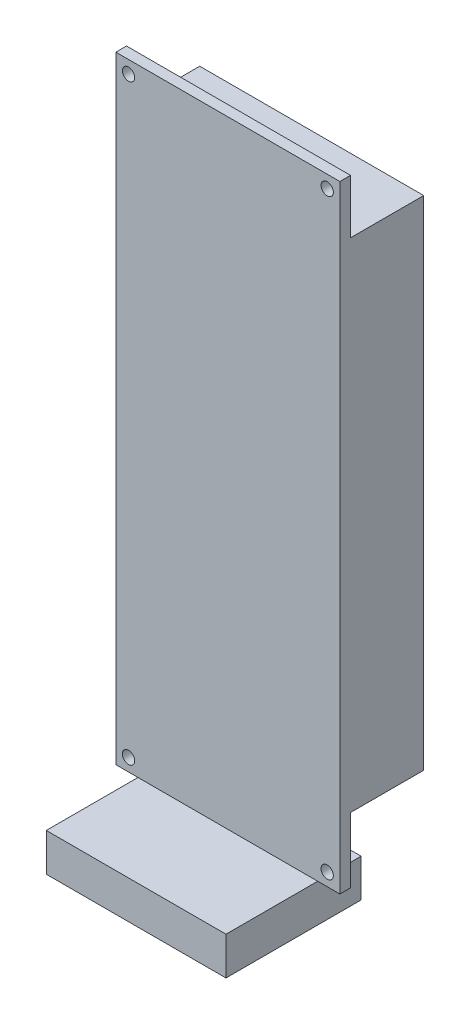
SolidWorks part; units mm, degrees
ref_plane "Front Plane" through (0, 0, 0) normal (0, 0, 1) x (1, 0, 0)
ref_plane "Top Plane" through (0, 0, 0) normal (0, 1, 0) x (1, 0, 0)
ref_plane "Right Plane" through (0, 0, 0) normal (1, 0, 0) x (0, 0, -1)
sketch "Sketch1" plane through (0, 0, 0) normal (0, 0, 1) x (1, 0, 0)
  line L1 (0, 0) -> (33.655, 0)
  line L2 (0, 0) -> (0, 92.71)
  line L3 (0, 92.71) -> (33.655, 92.71)
  line L4 (33.655, 0) -> (33.655, 92.71)
  circle A0 centre (1.905, 90.805) radius 0.925
  circle A1 centre (31.75, 90.805) radius 0.925
  circle A2 centre (1.905, 1.905) radius 0.925
  circle A3 centre (31.75, 1.905) radius 0.925
  dimension "D3" = 1.85
  dimension "D4" = 1.85
  dimension "D5" = 1.85
  dimension "D6" = 1.85
  dimension "D1" = 92.71
  dimension "D2" = 33.655
  dimension "D7" = 1.905
  dimension "D8" = 1.905
  dimension "D9" = 1.905
  dimension "D10" = 1.905
  dimension "D11" = 1.905
  dimension "D12" = 1.905
  dimension "D13" = 1.905
  dimension "D14" = 1.905
extrude "Boss-Extrude1" add sketch "Sketch1" along normal blind 1.6
sketch "Sketch2" plane through (0, 0, 0) normal (0, 0, -1) x (-1, 0, 0)
  line L0 (-33.655, 0) -> (-33.655, 92.71) construction
  line L1 (-33.655, 84.5804) -> (0, 84.5804)
  line L2 (-33.655, 84.5804) -> (-33.655, 9.8043)
  line L3 (-33.655, 9.8043) -> (0, 9.8043)
  line L4 (0, 84.5804) -> (0, 9.8043)
  line L5 (0, 92.71) -> (0, 0) construction
extrude "Boss-Extrude2" add sketch "Sketch2" along normal blind 11
sketch "Sketch3" plane through (0, 0, 0) normal (0, -1, 0) x (1, 0, 0)
  line L1 (30.325, -4.92) -> (3.325, -4.92)
  line L2 (30.325, -4.92) -> (30.325, 15.38)
  line L3 (30.325, 15.38) -> (3.325, 15.38)
  line L4 (3.325, -4.92) -> (3.325, 15.38)
  line L5 (33.655, -11) -> (33.655, 0) construction
  line L7 (33.655, 0) -> (0, 0) construction
  dimension "D1" = 27
  dimension "D2" = 20.3
  dimension "D3" = 3.33
  dimension "D4" = 4.92
extrude "Boss-Extrude3" add sketch "Sketch3" along normal blind 5.7
ref_plane "Plane1" through (33.655, 9.8043, -11) normal (-1, 0, 0) x (0, 0, 1)
sketch "Sketch5" plane through (0, -5.7, 0) normal (0, -1, 0) x (1, 0, 0)
  circle A0 centre (16.4938, 0.5991) radius 22
  dimension "D1" = 44
